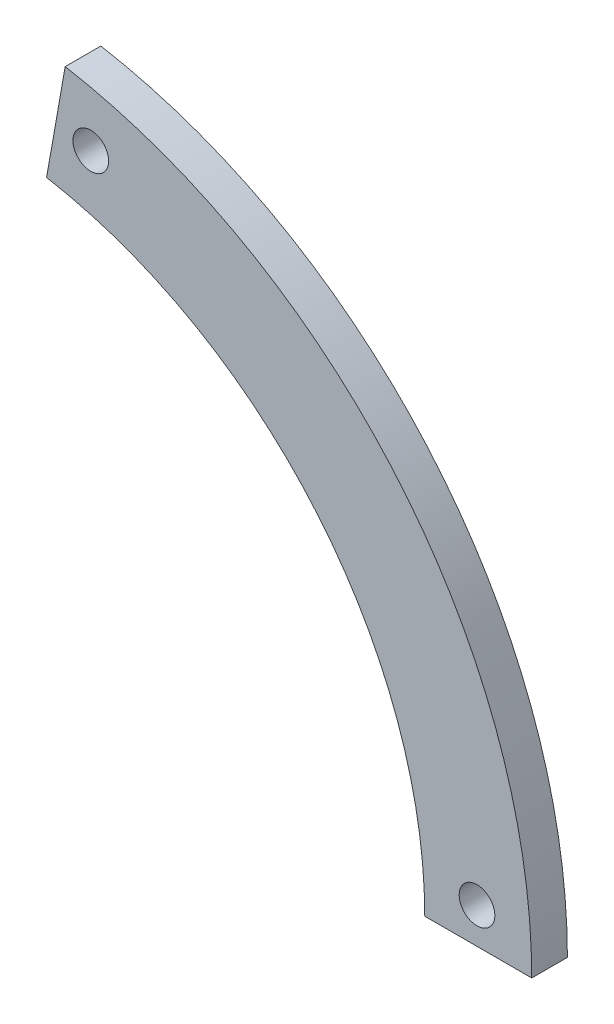
SolidWorks part; units mm, degrees
ref_plane "Alzado" through (0, 0, 0) normal (0, 0, 1) x (1, 0, 0)
ref_plane "Planta" through (0, 0, 0) normal (0, 1, 0) x (1, 0, 0)
ref_plane "Vista lateral" through (0, 0, 0) normal (1, 0, 0) x (0, 0, -1)
sketch "Croquis1" plane through (0, 0, 0) normal (0, 0, 1) x (1, 0, 0)
  line L0 (8.2483, 46.7784) -> (0, 0) construction
  line L1 (47.5, 0) -> (0, 0) construction
  line L2 (8.2483, 46.7784) -> (6.6855, 37.9151)
  line L3 (47.5, 0) -> (38.5, 0)
  line L4 (10.4031, 41.7226) -> (0, 0) construction
  line L5 (42.8952, 3) -> (0, 0) construction
  arc A2 (6.6855, 37.9151) -> (38.5, 0) centre (0, 0) cw
  arc A3 (8.2483, 46.7784) -> (47.5, 0) centre (0, 0) cw
  arc A4 (7.4669, 42.3467) -> (43, 0) centre (0, 0) cw construction
  circle A5 centre (42.8952, 3) radius 1.5
  circle A6 centre (10.4031, 41.7226) radius 1.5
  dimension "D1" = 38.5
  dimension "D2" = 47.5
  dimension "D4" = 3
  dimension "D6" = 3
  dimension "D3" = 80
  dimension "D5" = 3
  dimension "D7" = 3
  dimension "D8" = 71.999
extrude "Saliente-Extruir1" add sketch "Croquis1" along normal blind 3
equation "\"D6@Croquis1\"=\"D4@Croquis1\""
equation "\"D7@Croquis1\"=\"D5@Croquis1\""
